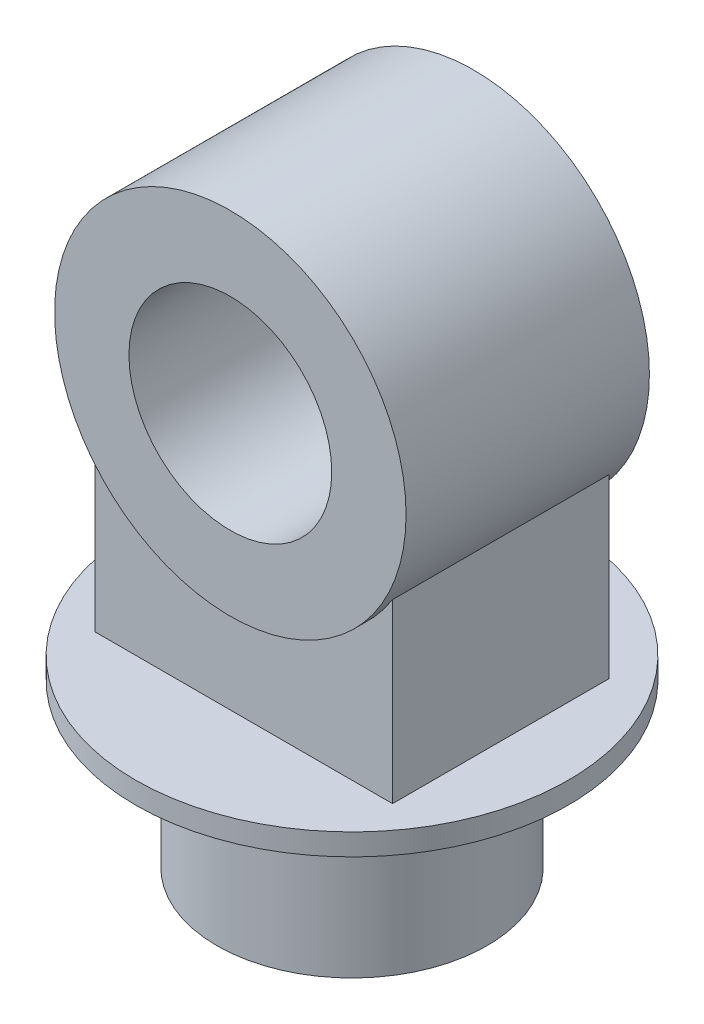
SolidWorks part; units mm, degrees
ref_plane "Front Plane" through (0, 0, 0) normal (0, 0, 1) x (1, 0, 0)
ref_plane "Top Plane" through (0, 0, 0) normal (0, 1, 0) x (1, 0, 0)
ref_plane "Right Plane" through (0, 0, 0) normal (1, 0, 0) x (0, 0, -1)
sketch "Sketch1" plane through (0, 0, 0) normal (0, 1, 0) x (1, 0, 0)
  circle A0 centre (0, 0) radius 100
extrude "Boss-Extrude1" add sketch "Sketch1" along normal blind 120
sketch "Sketch2" plane through (0, 120, 0) normal (0, 1, 0) x (1, 0, 0)
  circle A0 centre (0, 0) radius 160
extrude "Boss-Extrude2" add sketch "Sketch2" along normal blind 16
sketch "Sketch3" plane through (0, 0, 0) normal (0, 0, 1) x (1, 0, 0)
  line L0 (0, -6.8026) -> (0, 336)
  line L1 (160, 136) -> (-160, 136) construction
  circle A0 centre (0, 336) radius 130
  circle A1 centre (0, 336) radius 75
  dimension "D1" = 260
  dimension "D2" = 150
  dimension "D3" = 200
extrude "Boss-Extrude3" add sketch "Sketch3" along normal mid plane 180 separate body
sketch "Sketch4" plane through (0, 136, 0) normal (0, 1, 0) x (1, 0, 0)
  line L1 (110, -80) -> (-110, -80)
  line L2 (110, -80) -> (110, 80)
  line L3 (110, 80) -> (-110, 80)
  line L4 (-110, -80) -> (-110, 80)
  line L5 (110, -80) -> (-110, 80) construction
  line L6 (110, 80) -> (-110, -80) construction
  point P0 (0, 0)
  dimension "D1" = 220
  dimension "D2" = 160
extrude "Boss-Extrude4" add sketch "Sketch4" along normal up to next
